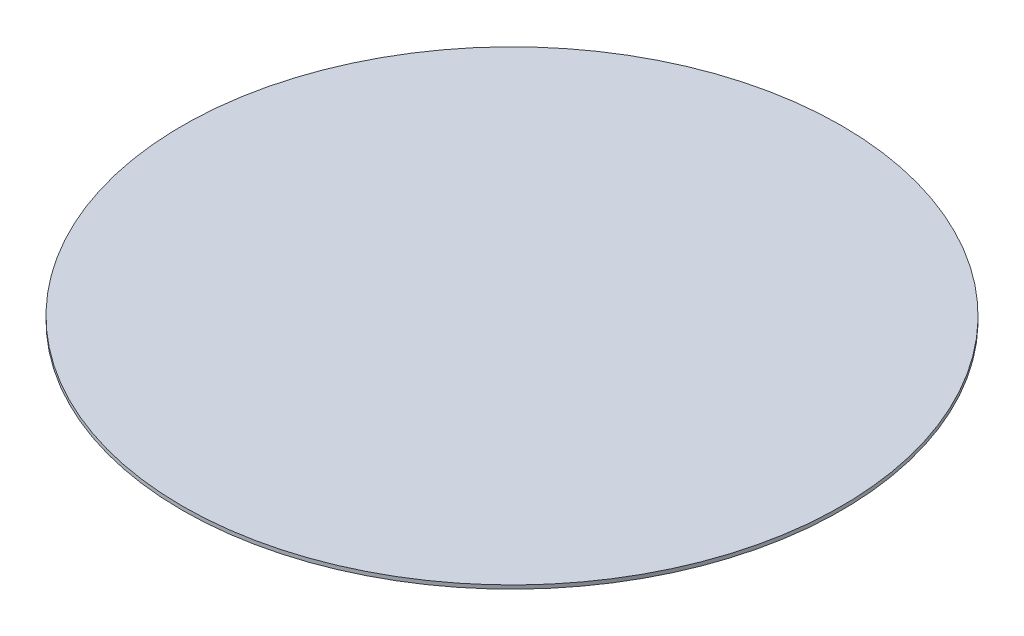
SolidWorks part; units mm, degrees
ref_plane "Front Plane" through (0, 0, 0) normal (0, 0, 1) x (1, 0, 0)
ref_plane "Top Plane" through (0, 0, 0) normal (0, 1, 0) x (1, 0, 0)
ref_plane "Right Plane" through (0, 0, 0) normal (1, 0, 0) x (0, 0, -1)
sketch "Sketch1" plane through (0, 0, 0) normal (0, 1, 0) x (1, 0, 0)
  circle A0 centre (0, 0) radius 57.15
  dimension "D1" = 114.3
extrude "Boss-Extrude1" add sketch "Sketch1" along normal blind 0.635
